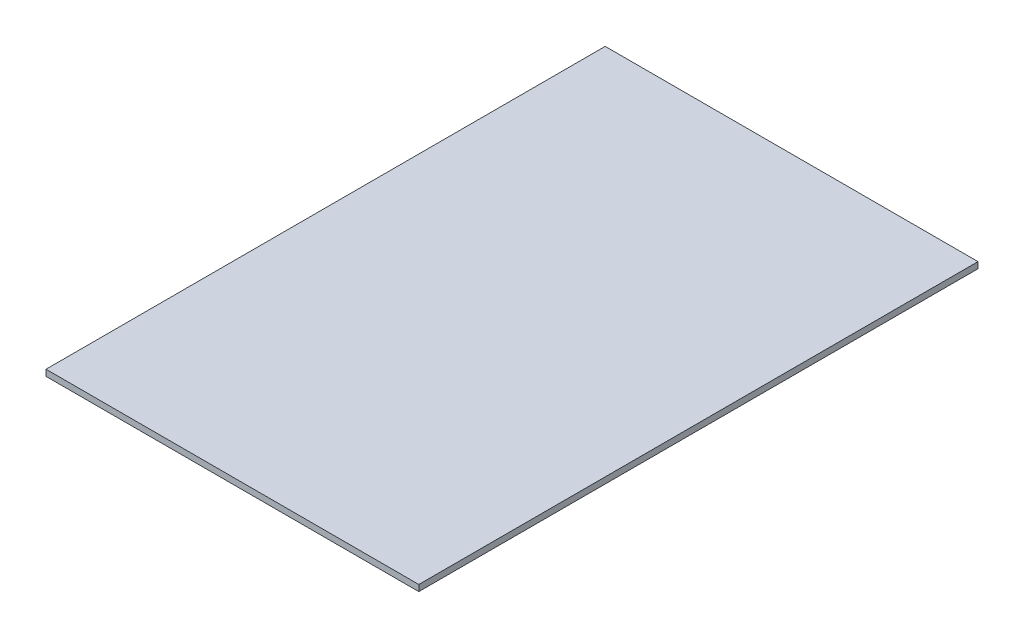
SolidWorks part; units mm, degrees
ref_plane "Front Plane" through (0, 0, 0) normal (0, 0, 1) x (1, 0, 0)
ref_plane "Top Plane" through (0, 0, 0) normal (0, 1, 0) x (1, 0, 0)
ref_plane "Right Plane" through (0, 0, 0) normal (1, 0, 0) x (0, 0, -1)
sketch "Sketch1" plane through (0, 0, 0) normal (0, 1, 0) x (1, 0, 0)
  line L1 (-60, 90) -> (60, 90)
  line L2 (-60, 90) -> (-60, -90)
  line L3 (-60, -90) -> (60, -90)
  line L4 (60, 90) -> (60, -90)
  line L5 (-60, 90) -> (60, -90) construction
  line L6 (-60, -90) -> (60, 90) construction
  point P0 (0, 0)
  dimension "D1" = 180
  dimension "D2" = 120
extrude "Boss-Extrude1" add sketch "Sketch1" along normal blind 2 contours L2 L3 L4 L1
